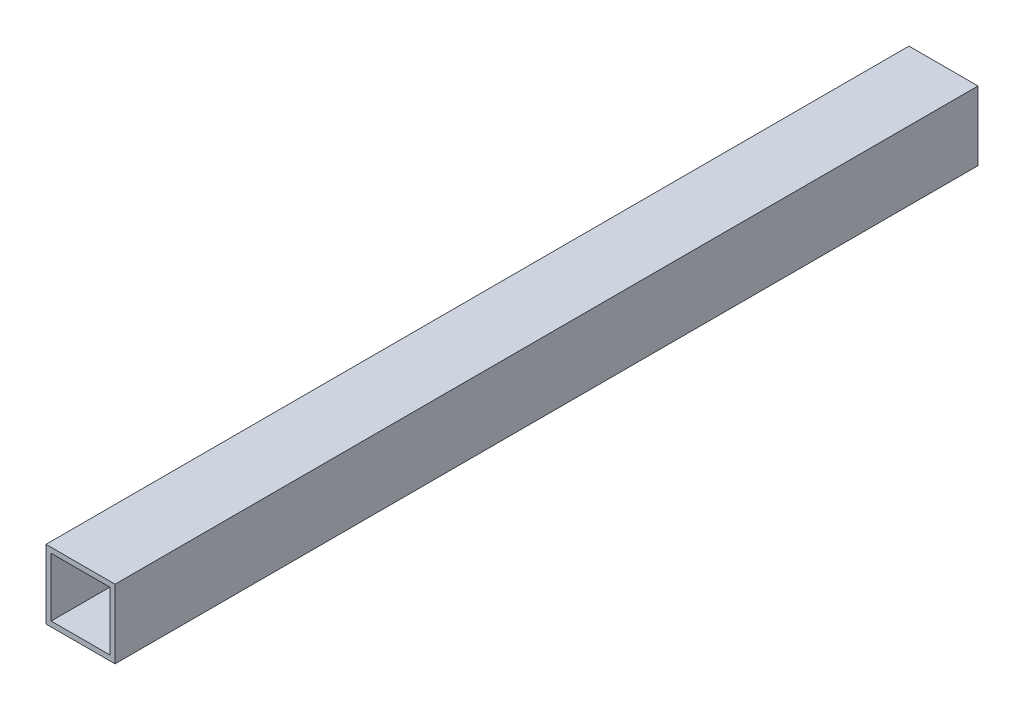
SolidWorks part; units mm, degrees
material "6063-O"
ref_plane "正面" through (0, 0, 0) normal (0, 0, 1) x (1, 0, 0)
ref_plane "平面" through (0, 0, 0) normal (0, 1, 0) x (1, 0, 0)
ref_plane "右側面" through (0, 0, 0) normal (1, 0, 0) x (0, 0, -1)
sketch "ｽｹｯﾁ1" plane through (0, 0, 0) normal (0, 0, 1) x (1, 0, 0)
  line L0 (-8.5, 8.5) -> (8.5, 8.5)
  line L1 (-10, 10) -> (10, 10)
  line L2 (-10, 10) -> (-10, -10)
  line L3 (-10, -10) -> (10, -10)
  line L4 (10, 10) -> (10, -10)
  line L5 (8.5, 8.5) -> (8.5, -8.5)
  line L6 (-8.5, -8.5) -> (8.5, -8.5)
  line L7 (-8.5, 8.5) -> (-8.5, -8.5)
  point P0 (0, 0)
  dimension "D1" = 20
  dimension "D2" = 20
  dimension "D3" = 1.5
extrude "ﾎﾞｽ - 押し出し1" add sketch "ｽｹｯﾁ1" along normal blind 250
